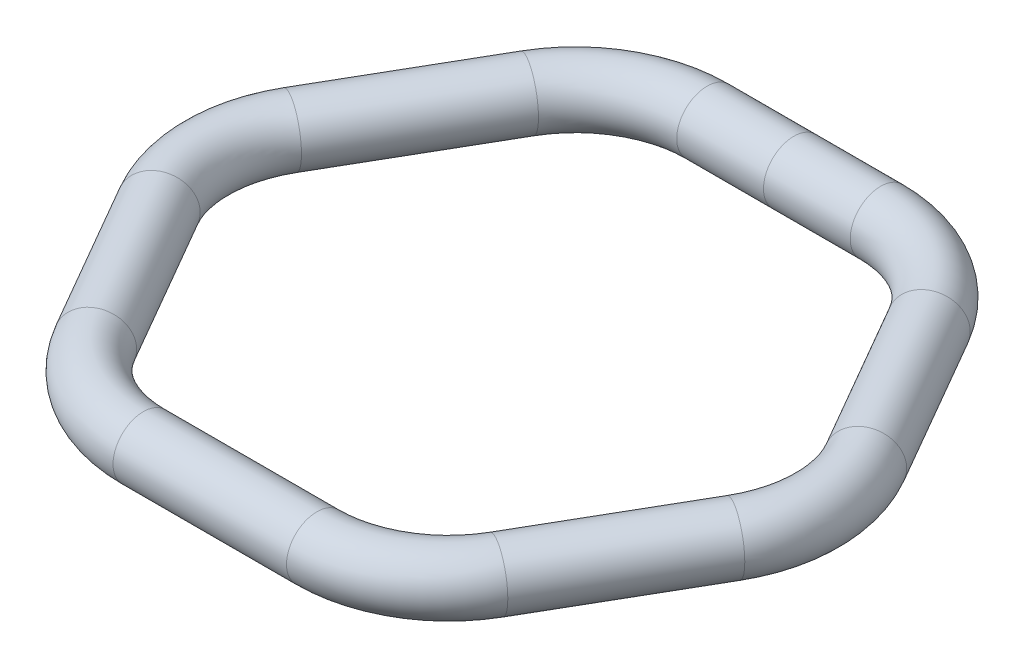
SolidWorks part; units mm, degrees
ref_plane "Front Plane" through (0, 0, 0) normal (0, 0, 1) x (1, 0, 0)
ref_plane "Top Plane" through (0, 0, 0) normal (0, 1, 0) x (1, 0, 0)
ref_plane "Right Plane" through (0, 0, 0) normal (1, 0, 0) x (0, 0, -1)
sketch "Sketch1" plane through (0, 0, 0) normal (0, 1, 0) x (1, 0, 0)
  line L1 (64.49, 12.5) -> (43.0703, 49.6)
  line L2 (21.4197, 62.1) -> (-21.4197, 62.1)
  line L3 (-43.0703, 49.6) -> (-64.49, 12.5)
  line L4 (-64.49, -12.5) -> (-43.0703, -49.6)
  line L5 (-21.4197, -62.1) -> (21.4197, -62.1)
  line L6 (43.0703, -49.6) -> (64.49, -12.5)
  circle A0 centre (0, 0) radius 62.1 construction
  arc A1 (-43.0703, -49.6) -> (-21.4197, -62.1) centre (-21.4197, -37.1) ccw
  arc A2 (21.4197, -62.1) -> (43.0703, -49.6) centre (21.4197, -37.1) ccw
  arc A3 (64.49, -12.5) -> (64.49, 12.5) centre (42.8394, 0) ccw
  arc A4 (43.0703, 49.6) -> (21.4197, 62.1) centre (21.4197, 37.1) ccw
  arc A5 (-21.4197, 62.1) -> (-43.0703, 49.6) centre (-21.4197, 37.1) ccw
  arc A6 (-64.49, 12.5) -> (-64.49, -12.5) centre (-42.8394, 0) ccw
  dimension "D2" = 25
  dimension "D1" = 124.2
sketch "Sketch2" plane through (0, 0, 0) normal (1, 0, 0) x (0, 0, -1)
  circle A4 centre (69.6, 0) radius 7.5
  point P2 (62.1, 0)
  dimension "D1" = 15
sweep "Sweep1" add profiles "Sketch2" path "Sketch1"
